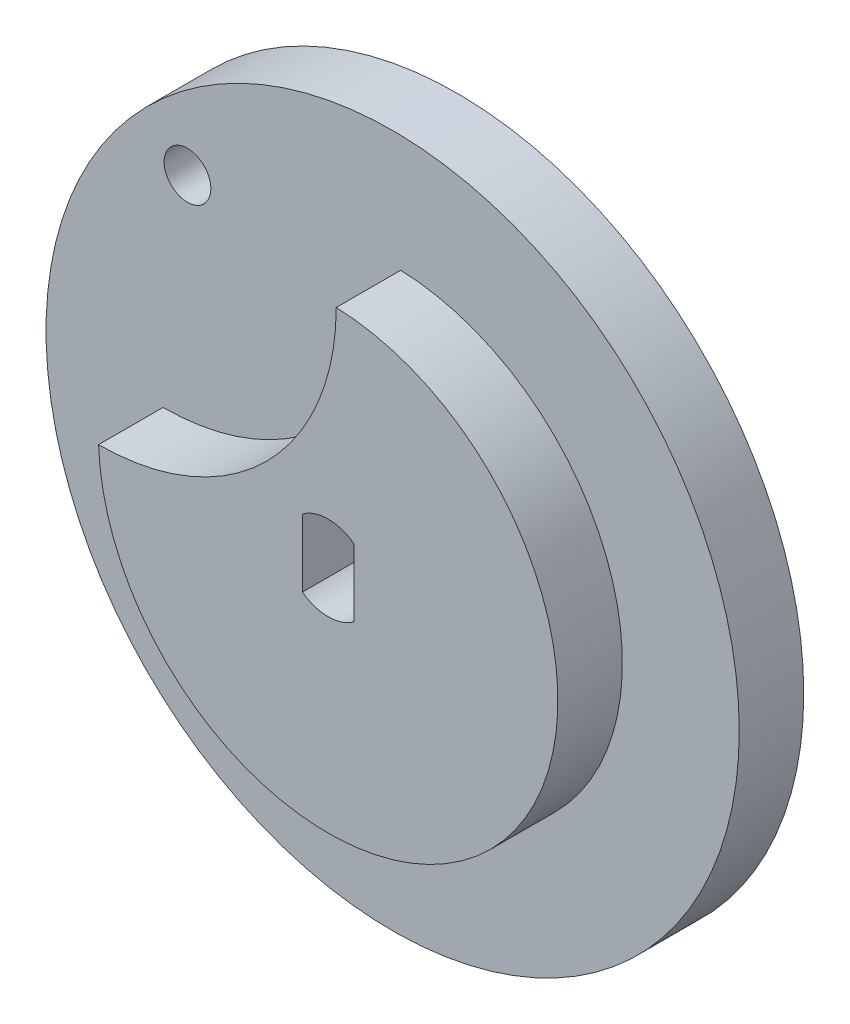
SolidWorks part; units mm, degrees
material "PLA"
ref_plane "Front Plane" through (0, 0, 0) normal (0, 0, 1) x (1, 0, 0)
ref_plane "Top Plane" through (0, 0, 0) normal (0, 1, 0) x (1, 0, 0)
ref_plane "Right Plane" through (0, 0, 0) normal (1, 0, 0) x (0, 0, -1)
sketch "Sketch2" plane through (0, 0, 0) normal (0, 0, 1) x (1, 0, 0)
  line L0 (-25.4558, 0) -> (-12.7279, 12.7279) construction
  line L1 (-12.7279, 12.7279) -> (0, 0) construction
  line L2 (-25.4558, 0) -> (0, 0) construction
  line L3 (-14.25, 0) -> (-14.25, 14.25) construction
  circle A0 centre (0, 0) radius 14.25 construction
  circle A1 centre (0, 0) radius 18 construction
  arc A2 (-14.2412, -0.4999) -> (0.4999, 14.2412) centre (-14.25, 14.25) ccw construction
  circle A3 centre (0, 0) radius 21.5 construction
  point P5 (-14.25, 0)
  dimension "D3" = 28.5
  dimension "D5" = 43
  dimension "D1" = 45
  dimension "D2" = 18
  dimension "D4" = 0.5
sketch "Sketch4" plane through (0, 0, 0) normal (0, 0, 1) x (1, 0, 0)
  line L0 (-1.6, 0) -> (1.6, 0) construction
  line L1 (-1.6, -2.1) -> (-1.6, 2.1)
  line L2 (1.6, -2.1) -> (1.6, 2.1)
  circle A0 centre (0, 0) radius 21.5
  circle A1 centre (0, 0) radius 21.5 construction
  circle A3 centre (-12.7279, 12.7279) radius 1.45
  arc A4 (-1.6, 2.1) -> (1.6, 2.1) centre (0, -0.0749) cw
  arc A5 (-1.6, -2.1) -> (1.6, -2.1) centre (0, 0.0749) ccw
  point P11 (0, 0)
  point P13 (-1.6, 0)
  point P17 (1.6, 0)
  dimension "D1" = 2.7
  dimension "D2" = 2.9
  dimension "D3" = 3.2
  dimension "D4" = 4.2
extrude "Boss-Extrude1" add sketch "Sketch4" along normal blind 4
sketch "Sketch5" plane through (0, 0, 4) normal (0, 0, 1) x (1, 0, 0)
  line L4 (-1.6, 0) -> (1.6, 0) construction
  line L5 (1.6, -2.1) -> (1.6, 2.1) construction
  line L6 (1.6, -2.1) -> (1.6, 2.1)
  line L7 (-1.6, -2.1) -> (-1.6, 2.1)
  arc A0 (-14.2412, -0.4999) -> (0.4999, 14.2412) centre (0, 0) ccw
  circle A1 centre (0, 0) radius 14.25 construction
  arc A4 (-14.2412, -0.4999) -> (0.4999, 14.2412) centre (-14.25, 14.25) ccw
  arc A5 (-14.2412, -0.4999) -> (0.4999, 14.2412) centre (-14.25, 14.25) ccw construction
  arc A8 (-1.6, 2.1) -> (1.6, 2.1) centre (0, -0.0749) cw
  arc A12 (1.6, 2.1) -> (-1.6, 2.1) centre (0, -0.0749) ccw construction
  arc A13 (-1.6, -2.1) -> (1.6, -2.1) centre (0, 0.0749) ccw
  point P17 (0, 0)
  point P35 (1.6, 0)
  point P39 (-1.6, 0)
  dimension "D1" = 2.7
extrude "Boss-Extrude2" add sketch "Sketch5" along normal blind 4
sketch "Sketch7" plane through (0, 0, 0) normal (0, 0, -1) x (-1, 0, 0)
  arc A2 (1.6, 2.1) -> (-1.6, 2.1) centre (0, -0.0749) ccw construction
  arc A3 (1.6, 2.1) -> (-1.6, 2.1) centre (0, -0.0749) ccw
  circle A4 centre (0, 0) radius 2.6251
  line M5 (1.6, 2.1) -> (1.6, -2.1)
  line M7 (-1.6, -2.1) -> (-1.6, 2.1)
extrude "Cut-Extrude1" cut sketch "Sketch7" against normal blind 1.5 contours A4 M7 | A4 M5
sketch "Sketch8" plane through (0, 0, 8) normal (0, 0, 1) x (1, 0, 0)
  circle A0 centre (0, 0) radius 14.25
  arc A1 (-14.2412, -0.4999) -> (0.4999, 14.2412) centre (0, 0) ccw construction
equation "\"1.5.00mm\"=10"
